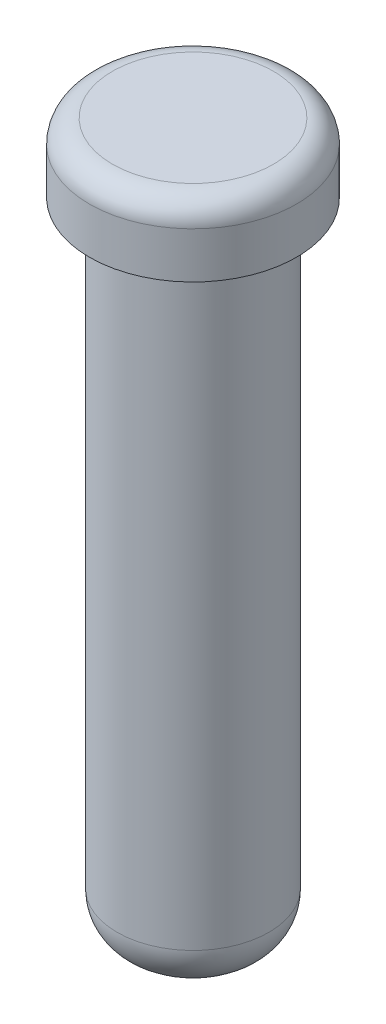
SolidWorks part; units mm, degrees
ref_plane "Front Plane" through (0, 0, 0) normal (0, 0, 1) x (1, 0, 0)
ref_plane "Top Plane" through (0, 0, 0) normal (0, 1, 0) x (1, 0, 0)
ref_plane "Right Plane" through (0, 0, 0) normal (1, 0, 0) x (0, 0, -1)
sketch "Sketch1" plane through (0, 0, 0) normal (0, 1, 0) x (1, 0, 0)
  circle A0 centre (0, 0) radius 1.65
  dimension "D1" = 3.3
extrude "Boss-Extrude1" add sketch "Sketch1" along normal blind 14
sketch "Sketch2" plane through (0, 14, 0) normal (0, 1, 0) x (1, 0, 0)
  circle A0 centre (0, 0) radius 2.25
  dimension "D1" = 4.5
extrude "Boss-Extrude2" add sketch "Sketch2" along normal blind 1.5
fillet "Fillet1" radius 0.5 1 edges at (0, 15.5, 2.25)
fillet "Fillet2" radius 1 1 edges at (0, 0, 1.65)
